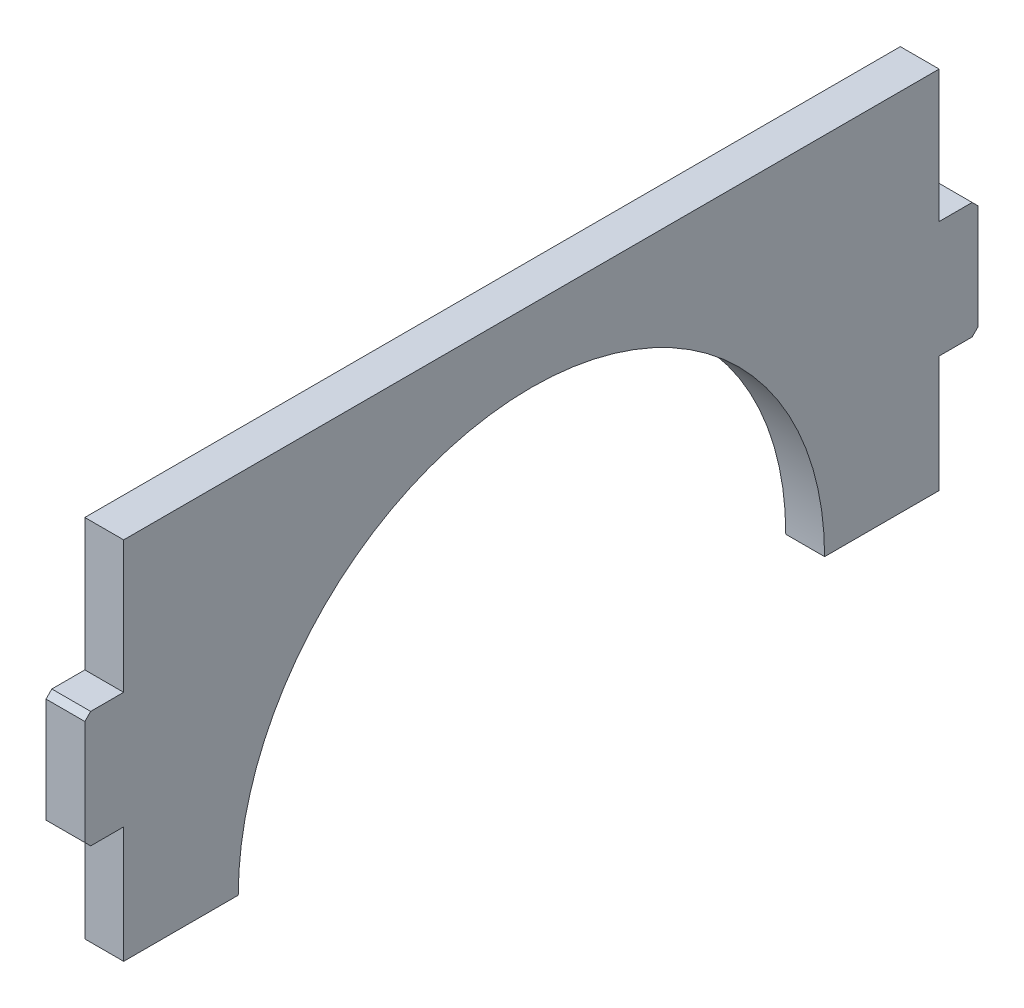
SolidWorks part; units mm, degrees
material "未指定"
ref_plane "正面" through (0, 0, 0) normal (0, 0, 1) x (1, 0, 0)
ref_plane "平面" through (0, 0, 0) normal (0, 1, 0) x (1, 0, 0)
ref_plane "右側面" through (0, 0, 0) normal (1, 0, 0) x (0, 0, -1)
sketch "ｽｹｯﾁ1" plane through (0, 0, 0) normal (1, 0, 0) x (0, 0, -1)
  line L0 (75.5, 0) -> (105, 0)
  line L1 (105, 0) -> (105, 94)
  line L2 (105, 94) -> (-105, 94)
  line L3 (-105, 94) -> (-105, 0)
  line L4 (-105, 0) -> (-75.5, 0)
  line L5 (0, 0) -> (0, 25) construction
  arc A0 (-75.5, 0) -> (75.5, 0) centre (0, 0) cw
  dimension "D3" = 75.5
  dimension "D1" = 210
  dimension "D2" = 94
extrude "板 外形切り出し" add sketch "ｽｹｯﾁ1" along normal mid plane 10
sketch "ｽｹｯﾁ2" plane through (0, 0, 0) normal (1, 0, 0) x (0, 0, -1)
  line L0 (-105, 30) -> (-115, 30)
  line L1 (-115, 30) -> (-115, 60)
  line L2 (-115, 60) -> (-105, 60)
  line L3 (-105, 60) -> (-105, 30)
  dimension "D1" = 115
  dimension "D2" = 105
  dimension "D3" = 30
  dimension "D4" = 60
extrude "ほぞ(右)" add sketch "ｽｹｯﾁ2" along normal mid plane 10
chamfer "ほぞ(右) 先端面取り" distance 1.5 angle 45 2 edges at (0, 60, 115) (0, 30, 115)
mirror "ほぞ(左)" about plane through (0, 0, 0) normal (0, 0, 1) of "ほぞ(右) 先端面取り", "ほぞ(右)"
equation "\"INNER_HALF_W\" = 105"
equation "\"D1@ｽｹｯﾁ1\" = 2 * ( \"INNER_HALF_W\" )"
equation "\"CLAMP_TOP\" = 94"
equation "\"D2@ｽｹｯﾁ1\" = \"CLAMP_TOP\""
equation "\"CRADLE_BORE\" = 151"
equation "\"D3@ｽｹｯﾁ1\" = \"CRADLE_BORE\" / 2"
equation "\"PLATE_T\" = 10"
equation "\"D1@板 外形切り出し\" = \"PLATE_T\""
equation "\"D1@ｽｹｯﾁ2\" = \"INNER_HALF_W\" + \"PLATE_T\""
equation "\"D2@ｽｹｯﾁ2\" = \"INNER_HALF_W\""
equation "\"TAB_Y\" = 45"
equation "\"TAB_W\" = 30"
equation "\"D3@ｽｹｯﾁ2\" = \"TAB_Y\" - \"TAB_W\" / 2"
equation "\"D4@ｽｹｯﾁ2\" = \"TAB_Y\" + \"TAB_W\" / 2"
equation "\"D1@ほぞ(右)\" = \"PLATE_T\""
equation "\"TAB_C\" = 1.5"
equation "\"D1@ほぞ(右) 先端面取り\" = \"TAB_C\""
